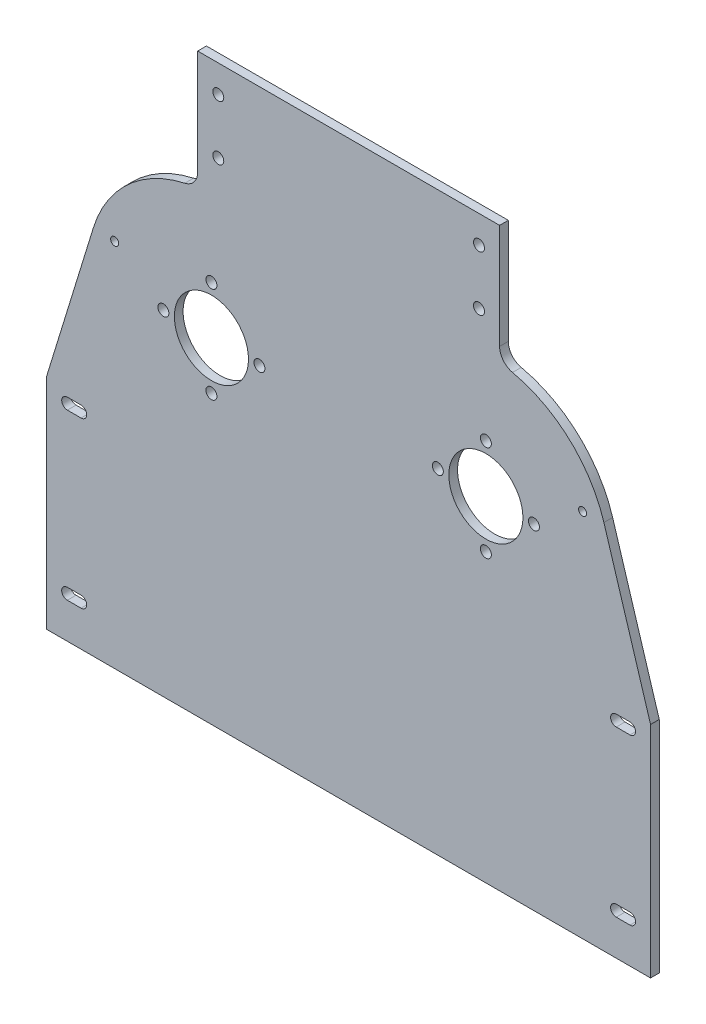
SolidWorks part; units mm, degrees
ref_plane "Front Plane" through (0, 0, 0) normal (0, 0, 1) x (1, 0, 0)
ref_plane "Top Plane" through (0, 0, 0) normal (0, 1, 0) x (1, 0, 0)
ref_plane "Right Plane" through (0, 0, 0) normal (1, 0, 0) x (0, 0, -1)
sketch "Sketch1" plane through (0, 0, 0) normal (0, 0, 1) x (1, 0, 0)
  line L1 (-100, -75) -> (100, -75)
  line L2 (-100, -75) -> (-100, 75)
  line L3 (-100, 75) -> (100, 75)
  line L4 (100, -75) -> (100, 75)
  line L5 (-100, -75) -> (100, 75) construction
  line L6 (-100, 75) -> (100, -75) construction
  line L8 (-47.5, 40) -> (47.5, 40) construction
  line L9 (0, 75) -> (0, -75) construction
  line L10 (-27, -44) -> (27, -44) construction
  line L11 (-27, -44) -> (-27, 28) construction
  line L12 (-27, 28) -> (27, 28) construction
  line L13 (27, -44) -> (27, 28) construction
  line L14 (-27, -44) -> (27, 28) construction
  line L15 (-27, 28) -> (27, -44) construction
  line L23 (-55, 70) -> (55, 70)
  line L24 (-55, 70) -> (-55, -70)
  line L25 (-55, -70) -> (55, -70)
  line L26 (55, 70) -> (55, -70)
  line L27 (-55, 70) -> (55, -70) construction
  line L28 (-55, -70) -> (55, 70) construction
  line L29 (-32.5, 70) -> (32.5, 70) construction
  line L30 (-32.5, 70) -> (-32.5, 55) construction
  line L31 (-32.5, 55) -> (32.5, 55) construction
  line L32 (32.5, 70) -> (32.5, 55) construction
  line L33 (-32.5, 70) -> (32.5, 55) construction
  line L34 (-32.5, 55) -> (32.5, 70) construction
  circle A2 centre (-47.5, 40) radius 2
  circle A3 centre (47.5, 40) radius 2
  circle A4 centre (-27, 28) radius 2 construction
  circle A5 centre (27, 28) radius 2 construction
  circle A6 centre (27, -44) radius 2 construction
  circle A7 centre (-27, -44) radius 2 construction
  circle A8 centre (-47.5, 60) radius 2
  circle A10 centre (47.5, 60) radius 2
  point P0 (0, 0)
  point P15 (0, 40)
  point P18 (0, -8)
  point P56 (0, 0)
  point P63 (0, 62.5)
  dimension "D3" = 4
  dimension "D4" = 20
  dimension "D5" = 4
  dimension "D8" = 4
  dimension "D1" = 150
  dimension "D2" = 200
  dimension "D6" = 72
  dimension "D7" = 54
  dimension "D14" = 30
  dimension "D15" = 140
  dimension "D16" = 110
  dimension "D17" = 95
  dimension "D18" = 12
  dimension "D19" = 15
  dimension "D20" = 65
extrude "Boss-Extrude1" add sketch "Sketch1" along normal blind 3.175 contours L23 L32 L31 L30 L24 L25 L26 A7 A6 A5 A4 A3 A2 | L2 L1 L4 L3
sketch "Sketch3" plane through (0, 0, 3.175) normal (0, 0, 1) x (1, 0, 0)
  line L0 (0, 31.3301) -> (0, 52.1198) construction
  line L1 (-50, -18) -> (-56.5118, 18.9303) construction
  line L2 (-50, -18) -> (50, -18) construction
  line L3 (-50, -18) -> (-87.5, -18) construction
  line L4 (-50, -18) -> (-85.2385, -5.1742) construction
  circle A0 centre (-50, -18) radius 45
  circle A1 centre (-50, -0.5) radius 2
  circle A2 centre (50, -18) radius 45
  circle A3 centre (-50, -18) radius 30
  circle A4 centre (50, -18) radius 30
  circle A5 centre (-47.5, 40) radius 2 construction
  circle A6 centre (-47.5, 40) radius 2
  circle A7 centre (47.5, 40) radius 2
  circle A8 centre (-32.5, -18) radius 2
  circle A9 centre (-50, -35.5) radius 2
  circle A10 centre (-67.5, -18) radius 2
  circle A11 centre (67.5, -18) radius 2
  circle A12 centre (50, -35.5) radius 2
  circle A13 centre (32.5, -18) radius 2
  circle A14 centre (50, -0.5) radius 2
  circle A15 centre (-50, -18) radius 13.5
  circle A16 centre (50, -18) radius 13.5
  circle A18 centre (-85.2385, -5.1742) radius 1.4732
  circle A19 centre (-50, -18) radius 37.5 construction
  circle A21 centre (85.2385, -5.1742) radius 1.4732
  point P28 (-50, -18)
  dimension "D1" = 100
  dimension "D2" = 90
  dimension "D3" = 58
  dimension "D4" = 60
  dimension "D5" = 4
  dimension "D7" = 35
  dimension "D8" = 27
  dimension "D9" = 7.5
  dimension "D6" = 4
  dimension "D11" = 80
  dimension "D12" = 20
extrude "Boss-Extrude3" add sketch "Sketch3" against normal up to surface (3.175 mm away) up to face at (0, 0, 0)
sketch "Sketch4" plane through (0, 0, 3.175) normal (0, 0, 1) x (1, 0, 0)
  line L0 (-110, -95) -> (-60, -95) construction
  line L1 (-60, -60) -> (-66.1555, -60)
  line L2 (-60, -60) -> (-60, -130)
  line L3 (-60, -130) -> (-115, -130)
  line L4 (-110, -60) -> (-110, -130)
  line L5 (-60, -60) -> (-110, -130) construction
  line L6 (-60, -130) -> (-110, -60) construction
  line L11 (-110, -60) -> (-93.0112, -4.7698)
  line L12 (-66.1555, -60) -> (-110, -60)
  line L13 (-60, -130) -> (-115, -130) construction
  line L14 (-60, -130) -> (-60, -121.7157)
  line L19 (-115, -130) -> (-110, -130)
  line L21 (-100, -95) -> (-100, -60) construction
  line L22 (-97.5, -65) -> (-102.5, -65) construction
  line L23 (-97.5, -67.05) -> (-102.5, -67.05)
  line L24 (-97.5, -62.95) -> (-102.5, -62.95)
  line L25 (-97.5, -125) -> (-102.5, -125) construction
  line L26 (-97.5, -122.95) -> (-102.5, -122.95)
  line L27 (-97.5, -127.05) -> (-102.5, -127.05)
  line L28 (-60, -60) -> (0, -60)
  line L29 (-60, -60) -> (-60, -130)
  line L30 (-60, -130) -> (0, -130)
  line L31 (0, -60) -> (0, -130)
  line L32 (-60, -60) -> (0, -130) construction
  line L33 (-60, -130) -> (0, -60) construction
  line L34 (-110, -130) -> (0, -130)
  line L35 (-110, -130) -> (-110, -140)
  line L36 (-110, -140) -> (0, -140)
  line L37 (0, -130) -> (0, -140)
  line L38 (-110, -130) -> (0, -140) construction
  line L39 (-110, -140) -> (0, -130) construction
  arc A0 (-55, 26.7214) -> (-55, -62.7214) centre (-50, -18) ccw construction
  arc A1 (-93.0112, -4.7698) -> (-66.1555, -60) centre (-50, -18) ccw
  circle A2 centre (-100, -65) radius 2.05 construction
  arc A3 (-97.5, -67.05) -> (-97.5, -62.95) centre (-97.5, -65) ccw
  arc A4 (-102.5, -62.95) -> (-102.5, -67.05) centre (-102.5, -65) ccw
  arc A5 (-97.5, -122.95) -> (-97.5, -127.05) centre (-97.5, -125) cw
  arc A6 (-102.5, -127.05) -> (-102.5, -122.95) centre (-102.5, -125) cw
  point P4 (-85, -95)
  point P12 (-55, -135)
  point P26 (-30, -95)
  point P32 (-100, -65)
  point P40 (-100, -125)
  dimension "D7" = 4.1
  dimension "D8" = 2.05
  dimension "D1" = 60
  dimension "D2" = 60
  dimension "D3" = 70
  dimension "D4" = 50
  dimension "D5" = 10
  dimension "D6" = 10
  dimension "D9" = 5
  dimension "D10" = 5
extrude "Boss-Extrude5" add sketch "Sketch4" against normal up to surface (3.175 mm away)
mirror "Mirror2" about plane through (0, 0, 0) normal (1, 0, 0) of "Boss-Extrude5"
fillet "Fillet1" radius 6 2 edges at (55, 26.7214, 1.5875) (-55, 26.7214, 1.5875)
ref_plane "Plane1" through (-55, -5.4601, 3.175) normal (0, -1, 0) x (-1, 0, 0)
sketch "Sketch6" plane through (0, 0, 3.175) normal (0, 0, 1) x (1, 0, 0)
  circle A0 centre (32.5, -18) radius 2 construction
  circle A1 centre (50, -0.5) radius 2 construction
  circle A2 centre (67.5, -18) radius 2 construction
  circle A3 centre (50, -18) radius 13.5 construction
  circle A4 centre (50, -35.5) radius 2 construction
  circle A5 centre (-50, -18) radius 13.5 construction
  circle A6 centre (-67.5, -18) radius 2 construction
  circle A7 centre (-50, -35.5) radius 2 construction
  circle A8 centre (-32.5, -18) radius 2 construction
  circle A9 centre (-50, -0.5) radius 2 construction
  circle A10 centre (32.5, -18) radius 2
  circle A11 centre (50, -0.5) radius 2
  circle A12 centre (67.5, -18) radius 2
  circle A13 centre (50, -18) radius 13.5
  circle A14 centre (50, -35.5) radius 2
  circle A15 centre (-50, -18) radius 13.5
  circle A16 centre (-67.5, -18) radius 2
  circle A17 centre (-50, -35.5) radius 2
  circle A18 centre (-32.5, -18) radius 2
  circle A19 centre (-50, -0.5) radius 2
extrude "Cut-Extrude1" cut sketch "Sketch6" against normal blind 10
